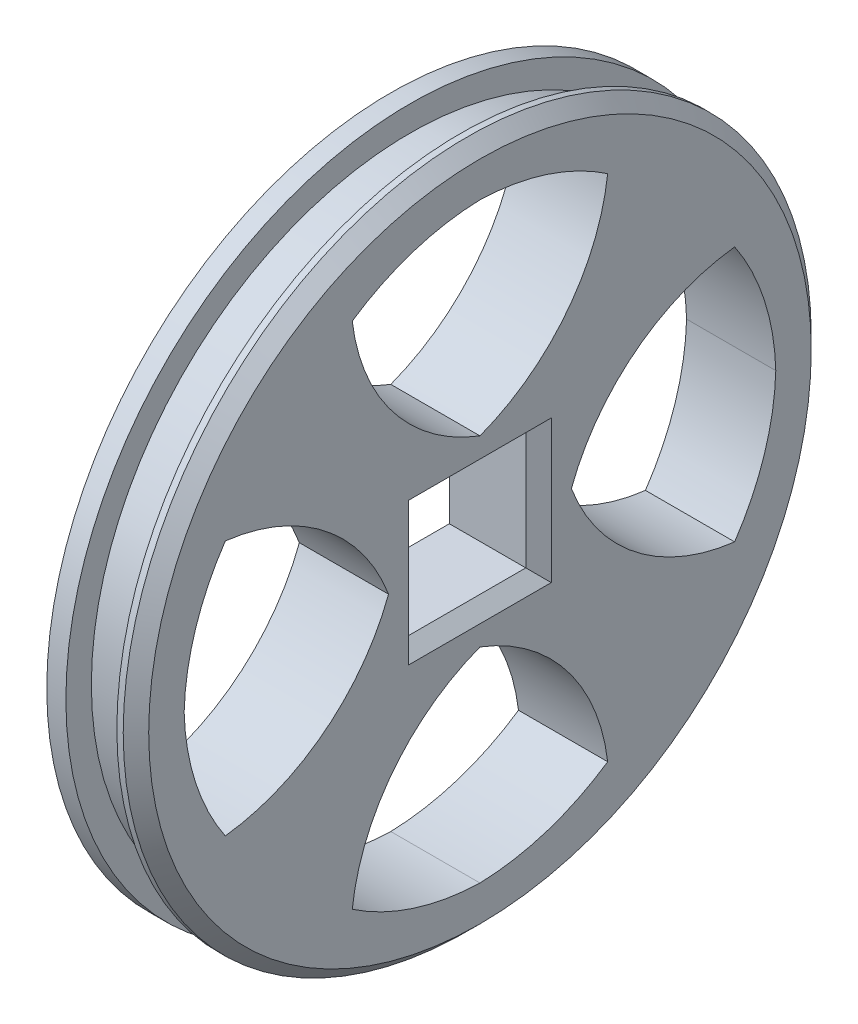
SolidWorks part; units mm, degrees
ref_plane "Front Plane" through (0, 0, 0) normal (0, 0, 1) x (1, 0, 0)
ref_plane "Top Plane" through (0, 0, 0) normal (0, 1, 0) x (1, 0, 0)
ref_plane "Right Plane" through (0, 0, 0) normal (1, 0, 0) x (0, 0, -1)
sketch "Sketch1" plane through (0, 0, 0) normal (1, 0, 0) x (0, 0, -1)
  circle A0 centre (0, 0) radius 13.5
  dimension "D1" = 27
extrude "Boss-Extrude1" add sketch "Sketch1" along normal mid plane 3.5
sketch "Sketch2" plane through (0, 0, 0) normal (1, 0, 0) x (0, 0, -1)
  line L0 (0, 0) -> (0, 14.8201) construction
  arc A0 (0, 3.5875) -> (-5.0122, 9.994) centre (2.7702, 10.9187) cw
  arc A1 (-5.0122, 9.994) -> (0, 11.6087) centre (0.2591, 2.218) cw
  arc A2 (5.0122, 9.994) -> (0, 11.6087) centre (-0.2591, 2.218) ccw
  arc A3 (0, 3.5875) -> (5.0122, 9.994) centre (-2.7702, 10.9187) ccw
extrude "Cut-Extrude1" cut sketch "Sketch2" along normal through all both and the other way through all
pattern_circular "CirPattern1" count 4 over 360 about axis through (0, 0, 0) along (1, 0, 0) of "Cut-Extrude1"
sketch "Sketch3" plane through (0, 0, 0) normal (1, 0, 0) x (0, 0, -1)
  line L1 (2.2981, -2.2981) -> (-2.2981, -2.2981)
  line L2 (2.2981, -2.2981) -> (2.2981, 2.2981)
  line L3 (2.2981, 2.2981) -> (-2.2981, 2.2981)
  line L4 (-2.2981, -2.2981) -> (-2.2981, 2.2981)
  line L5 (2.2981, -2.2981) -> (-2.2981, 2.2981) construction
  line L6 (2.2981, 2.2981) -> (-2.2981, -2.2981) construction
  circle A0 centre (0, 0) radius 3.25 construction
  dimension "D1" = 6.5
extrude "Cut-Extrude2" cut sketch "Sketch3" along normal through all both and the other way through all
chamfer "Chamfer1" distance 0.5 angle 45 5 edges at (1.75, 0, 2.2981) (1.75, -2.2981, 0) (1.75, 2.2981, 0) (1.75, 0, -2.2981) (1.75, 0, -13.5)
sketch "Sketch4" plane through (0, 0, 0) normal (1, 0, 0) x (0, 0, -1)
  circle A0 centre (0, 0) radius 13.5
  circle A1 centre (0, 0) radius 12.5
  circle A2 centre (0, 0) radius 13.5 construction
  dimension "D1" = 1
extrude "Cut-Extrude3" cut sketch "Sketch4" against normal mid plane 2
equation "\"axis_diameter\"=5.66"
equation "\"padding\"=0.5"
